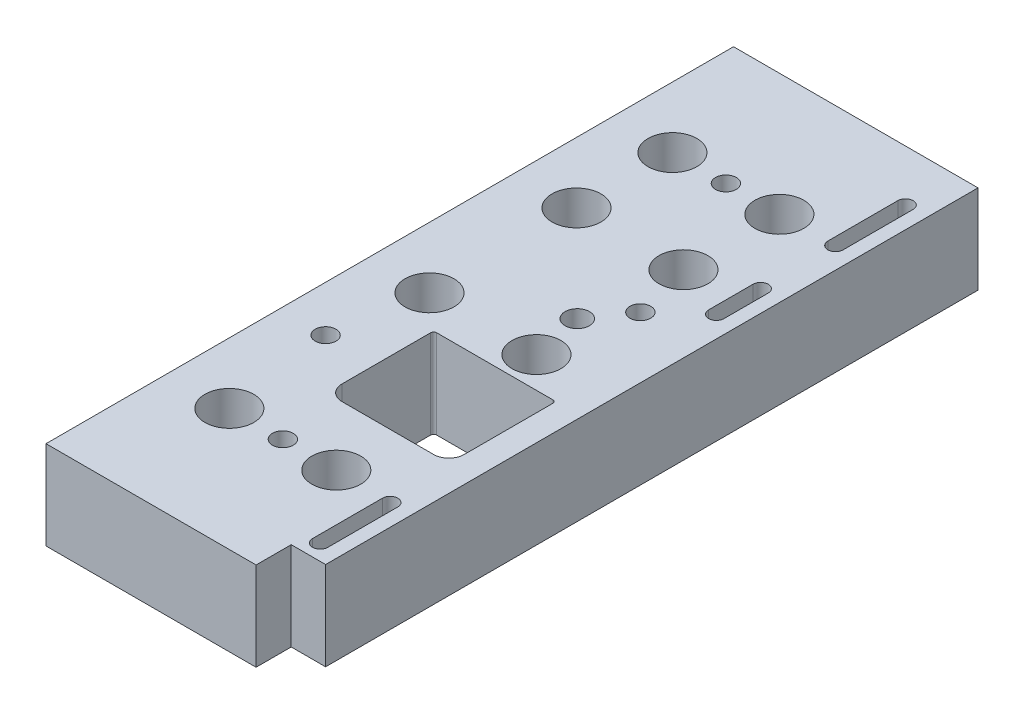
SolidWorks part; units mm, degrees
material "Plain Carbon Steel"
ref_plane "Front Plane" through (0, 0, 0) normal (0, 0, 1) x (1, 0, 0)
ref_plane "Top Plane" through (0, 0, 0) normal (0, 1, 0) x (1, 0, 0)
ref_plane "Right Plane" through (0, 0, 0) normal (1, 0, 0) x (0, 0, -1)
sketch "Sketch1" plane through (0, 0, 0) normal (0, 1, 0) x (1, 0, 0)
  line L1 (-40, -112.5) -> (40, -112.5)
  line L2 (-40, -112.5) -> (-40, 112.5)
  line L3 (-40, 112.5) -> (40, 112.5)
  line L4 (40, -112.5) -> (40, 112.5)
  line L5 (-40, -112.5) -> (40, 112.5) construction
  line L6 (-40, 112.5) -> (40, -112.5) construction
  point P0 (0, 0)
  dimension "D1" = 225
  dimension "D2" = 80
extrude "Boss-Extrude1" add sketch "Sketch1" against normal blind 29
sketch "Sketch2" plane through (0, 0, 0) normal (0, 1, 0) x (1, 0, 0)
  line L0 (30.5, 72.87) -> (30.5, 95.77) construction
  line L1 (35.5, 95.77) -> (35.5, 72.87) construction
  line L2 (30.5, 33.86) -> (30.5, 48.36) construction
  line L3 (35.5, 48.36) -> (35.5, 33.86) construction
  line L4 (31.5, -47.14) -> (31.5, -18.14) construction
  line L5 (30.5, -17.14) -> (-7.5, -17.14) construction
  line L6 (-8.5, -18.14) -> (-8.5, -47.14) construction
  line L7 (-3.5, -52.14) -> (26.5, -52.14) construction
  line L8 (30.5, -95.77) -> (30.5, -72.87) construction
  line L9 (35.5, -72.87) -> (35.5, -95.77) construction
  line L10 (30.5, 72.87) -> (30.5, 95.77)
  line L11 (35.5, 95.77) -> (35.5, 72.87)
  line L12 (30.5, 33.86) -> (30.5, 48.36)
  line L13 (35.5, 48.36) -> (35.5, 33.86)
  line L14 (31.5, -47.14) -> (31.5, -18.14)
  line L15 (30.5, -17.14) -> (-7.5, -17.14)
  line L16 (-8.5, -18.14) -> (-8.5, -47.14)
  line L17 (-3.5, -52.14) -> (26.5, -52.14)
  line L18 (30.5, -95.77) -> (30.5, -72.87)
  line L19 (35.5, -72.87) -> (35.5, -95.77)
  arc A0 (30.5, 72.87) -> (35.5, 72.87) centre (33, 72.87) ccw construction
  arc A1 (35.5, 95.77) -> (30.5, 95.77) centre (33, 95.77) ccw construction
  arc A2 (30.5, 33.86) -> (35.5, 33.86) centre (33, 33.86) ccw construction
  arc A3 (35.5, 48.36) -> (30.5, 48.36) centre (33, 48.36) ccw construction
  arc A4 (26.5, -52.14) -> (31.5, -47.14) centre (26.5, -47.14) ccw construction
  arc A5 (31.5, -18.14) -> (30.5, -17.14) centre (30.5, -18.14) ccw construction
  arc A6 (-7.5, -17.14) -> (-8.5, -18.14) centre (-7.5, -18.14) ccw construction
  arc A7 (-8.5, -47.14) -> (-3.5, -52.14) centre (-3.5, -47.14) ccw construction
  arc A8 (35.5, -72.87) -> (30.5, -72.87) centre (33, -72.87) ccw construction
  arc A9 (30.5, -95.77) -> (35.5, -95.77) centre (33, -95.77) ccw construction
  arc A10 (30.5, 72.87) -> (35.5, 72.87) centre (33, 72.87) ccw
  arc A11 (35.5, 95.77) -> (30.5, 95.77) centre (33, 95.77) ccw
  arc A12 (30.5, 33.86) -> (35.5, 33.86) centre (33, 33.86) ccw
  arc A13 (35.5, 48.36) -> (30.5, 48.36) centre (33, 48.36) ccw
  arc A14 (26.5, -52.14) -> (31.5, -47.14) centre (26.5, -47.14) ccw
  arc A15 (31.5, -18.14) -> (30.5, -17.14) centre (30.5, -18.14) ccw
  arc A16 (-7.5, -17.14) -> (-8.5, -18.14) centre (-7.5, -18.14) ccw
  arc A17 (-8.5, -47.14) -> (-3.5, -52.14) centre (-3.5, -47.14) ccw
  arc A18 (35.5, -72.87) -> (30.5, -72.87) centre (33, -72.87) ccw
  arc A19 (30.5, -95.77) -> (35.5, -95.77) centre (33, -95.77) ccw
extrude "Cut-Extrude1" cut sketch "Sketch2" against normal up to next
sketch "Sketch3" plane through (0, 0, 0) normal (0, 1, 0) x (1, 0, 0)
  line L0 (-40, -112.5) -> (40, -112.5) construction
  line L2 (-40, 112.5) -> (-40, -112.5) construction
  line L3 (30.5, 41.11) -> (-40, 41.11) construction
  line L4 (30.5, 48.36) -> (30.5, 33.86) construction
  line L5 (40, 112.5) -> (-40, 112.5) construction
  line L7 (40, -112.5) -> (40, 112.5) construction
  circle A0 centre (15, 72.5) radius 8
  circle A1 centre (15, 41.11) radius 8
  circle A2 centre (15, -7) radius 8
  circle A3 centre (15, -72.5) radius 8
  circle A4 centre (-20, -72.5) radius 8
  circle A5 centre (-20, -7) radius 8
  circle A6 centre (-20, 41.11) radius 8
  circle A7 centre (-20, 72.5) radius 8
  dimension "D1" = 16
  dimension "D2" = 25
  dimension "D3" = 20
  dimension "D4" = 40
  dimension "D5" = 40
  dimension "D6" = 7
extrude "Cut-Extrude2" cut sketch "Sketch3" against normal blind 20
hole_wizard "M8 Tapped Hole1" positions "Sketch18" profile "Sketch10" tap size "M8" standard "ISO"
sketch "Sketch18" plane through (0, 0, 0) normal (0, 1, 0) x (1, 0, 0)
  line L0 (-20, 72.5) -> (15, 72.5) construction
  line L2 (-20, -72.5) -> (15, -72.5) construction
  point P0 (-25, -36)
  point P2 (20, 22)
  point P4 (-2.5, 72.5)
  point P6 (-2.5, -72.5)
  dimension "D1" = 22
  dimension "D2" = 25
  dimension "D3" = 20
  dimension "D7" = 36
sketch "Sketch10" plane through (-25, 0, 36) normal (1, 0, 0) x (0, 0, 1)
  line L0 (0, 0) -> (0, 21.7929)
  line L1 (0, 21.7929) -> (3.4, 19.75)
  line L2 (3.4, 19.75) -> (3.4, 0)
  line L5 (3.4, 0) -> (0, 0)
  line L10 (0, 21.7929) -> (-3.4, 19.75) construction
  line L11 (0, -6.35) -> (0, 107.95) construction
  dimension "Tap Drill Dia." = 6.8
  dimension "Tap Drill Depth" = 19.75
  dimension "Drill Angle" = 118
cosmetic thread "Hole Thread5" parameters "D1"=16, "D2"=8
cosmetic thread "Hole Thread6" parameters "D1"=16, "D2"=8
cosmetic thread "Hole Thread7" parameters "D1"=16, "D2"=8
cosmetic thread "Hole Thread8" parameters "D1"=16, "D2"=8
sketch "Sketch15" plane through (0, 0, 0) normal (0, 1, 0) x (1, 0, 0)
  line L0 (-40, -112.5) -> (40, -112.5) construction
  line L1 (28.75, -112.5) -> (40.75, -112.5)
  line L2 (28.75, -112.5) -> (28.75, -101)
  line L3 (28.75, -101) -> (40.75, -101)
  line L4 (40.75, -112.5) -> (40.75, -101)
  line L5 (29.75, -115) -> (29.75, -102.5) construction
  line L6 (30.25, -102) -> (39.25, -102) construction
  line L7 (39.75, -102.5) -> (39.75, -115) construction
  dimension "D1" = 1
  dimension "D2" = 1
  dimension "D3" = 1
extrude "Cut-Extrude3" cut sketch "Sketch15" against normal up to next
sketch "Sketch16" plane through (0, -29, 0) normal (0, -1, 0) x (1, 0, 0)
  circle A0 centre (11.5, 100) radius 8.5
  circle A1 centre (11.5, -100) radius 8.5
  dimension "D1" = 17
extrude "Cut-Extrude4" cut sketch "Sketch16" against normal blind 5
sketch "Sketch17" plane through (0, 0, 0) normal (0, 1, 0) x (1, 0, 0)
  circle A0 centre (11.5, 9.86) radius 4
  dimension "D1" = 8
extrude "Cut-Extrude5" cut sketch "Sketch17" against normal up to next
